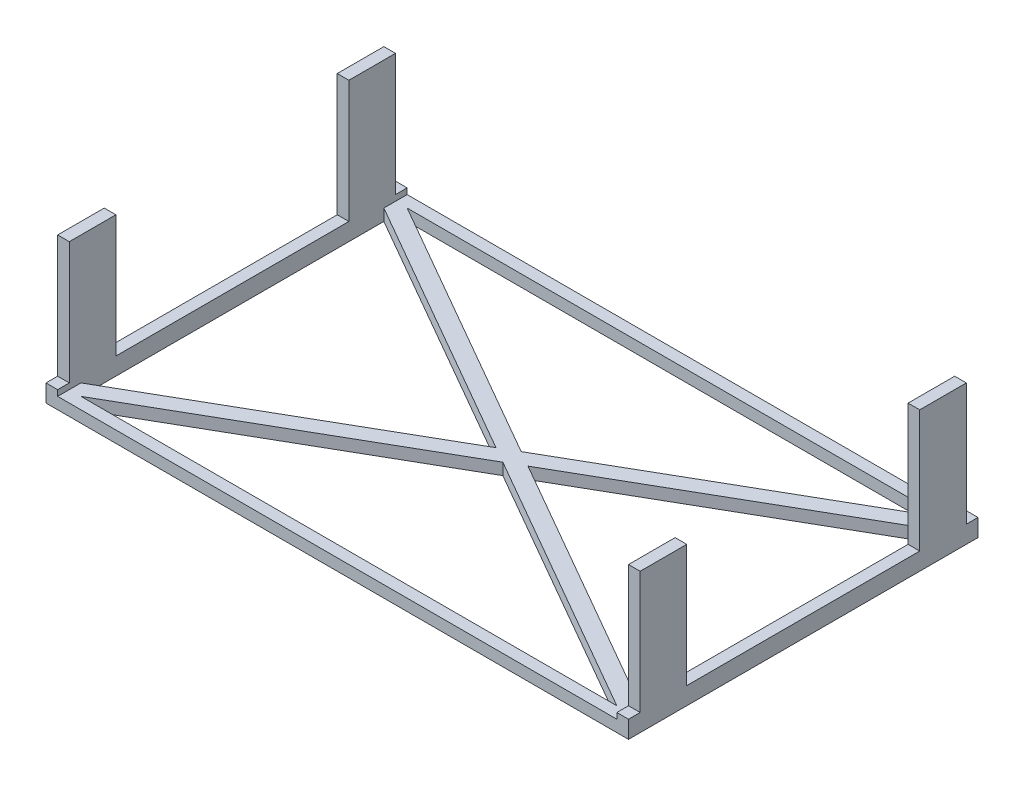
SolidWorks part; units mm, degrees
material "ABS"
ref_plane "前视基准面" through (0, 0, 0) normal (0, 0, 1) x (1, 0, 0)
ref_plane "上视基准面" through (0, 0, 0) normal (0, 1, 0) x (1, 0, 0)
ref_plane "右视基准面" through (0, 0, 0) normal (1, 0, 0) x (0, 0, -1)
sketch "base" plane through (0, 0, 0) normal (0, 1, 0) x (1, 0, 0)
  line L1 (0, 0) -> (500, 0)
  line L2 (0, 0) -> (0, -300)
  line L3 (0, -300) -> (500, -300)
  line L4 (500, 0) -> (500, -300)
  dimension "D1" = 500
  dimension "D2" = 300
  dimension "D3" = 0
extrude "凸台-拉伸1" add sketch "base" along normal blind 120 contours L1 L4 L3 L2
sketch "草图1" plane through (0, 0, 0) normal (0, 0, -1) x (-1, 0, 0)
  line L1 (-490, 120) -> (-10, 120)
  line L2 (-490, 120) -> (-490, 10)
  line L3 (-490, 10) -> (-10, 10)
  line L4 (-10, 120) -> (-10, 10)
  line L5 (0, 120) -> (-500, 120) construction
  dimension "D1" = 10
  dimension "D2" = 10
  dimension "D3" = 10
extrude "切除-拉伸1" cut sketch "草图1" against normal through all
sketch "草图2" plane through (0, 0, 0) normal (0, -1, 0) x (1, 0, 0)
  line L0 (10, 280) -> (10, 20)
  line L1 (10, 20) -> (236.2963, 150)
  line L2 (236.2963, 150) -> (10, 280)
  line L3 (20, 290) -> (480, 290)
  line L4 (480, 290) -> (250, 157.8723)
  line L5 (250, 157.8723) -> (20, 290)
  line L6 (263.7037, 150) -> (490, 280)
  line L7 (490, 280) -> (490, 20)
  line L8 (490, 20) -> (263.7037, 150)
  line L9 (250, 142.1277) -> (20, 10)
  line L10 (20, 10) -> (480, 10)
  line L11 (480, 10) -> (250, 142.1277)
  point P0 (26.7023, 290)
  dimension "D1" = 10
  dimension "D2" = 10
  dimension "D3" = 20
  dimension "D4" = 20
  dimension "D8" = 10
  dimension "D9" = 10
extrude "切除-拉伸2" cut sketch "草图2" against normal through all
sketch "草图3" plane through (0, 0, 0) normal (-1, 0, 0) x (0, 0, 1)
  line L0 (0, 120) -> (300, 120) construction
  line L1 (50, 120) -> (250, 120)
  line L2 (50, 120) -> (50, 15)
  line L3 (50, 15) -> (250, 15)
  line L4 (250, 120) -> (250, 15)
  line L5 (0, 120) -> (0, 0) construction
  line L6 (0, 120) -> (10, 120)
  line L7 (0, 120) -> (0, 15)
  line L8 (0, 15) -> (10, 15)
  line L9 (10, 120) -> (10, 15)
  line L10 (290, 120) -> (300, 120)
  line L11 (290, 120) -> (290, 15)
  line L12 (290, 15) -> (300, 15)
  line L13 (300, 120) -> (300, 15)
  line L14 (300, 120) -> (300, 0) construction
  point P14 (0, 0)
  point P19 (18.6925, 15)
  dimension "D1" = 15
  dimension "D2" = 40
  dimension "D3" = 40
  dimension "D4" = 10
extrude "切除-拉伸3" cut sketch "草图3" against normal through all
